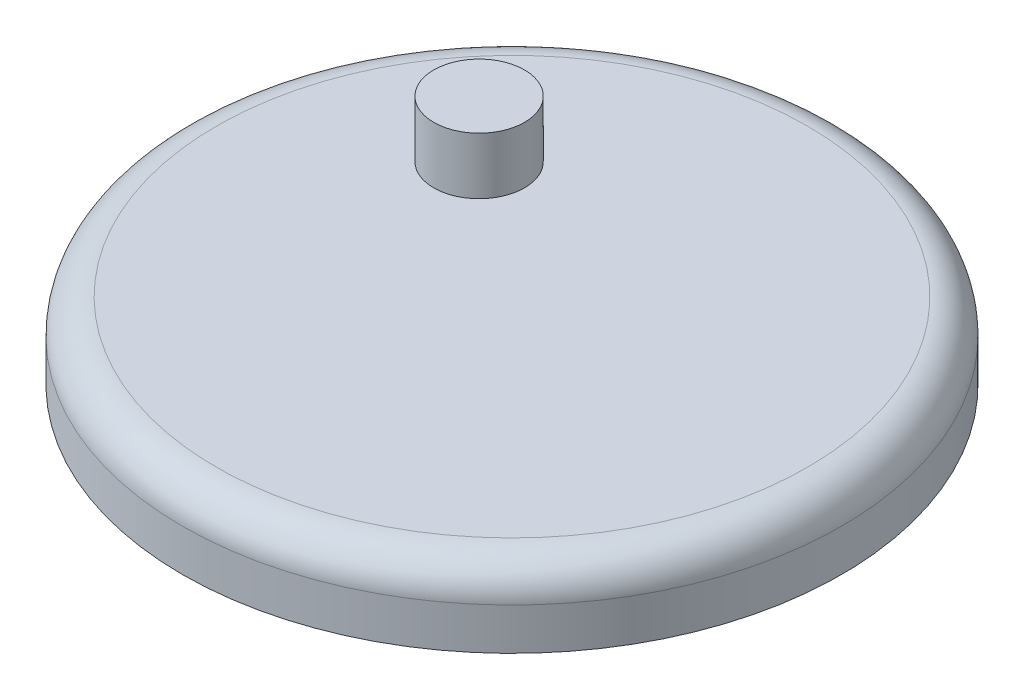
SolidWorks part; units mm, degrees
ref_plane "Front" through (0, 0, 0) normal (0, 0, 1) x (1, 0, 0)
ref_plane "Top" through (0, 0, 0) normal (0, 1, 0) x (1, 0, 0)
ref_plane "Right" through (0, 0, 0) normal (1, 0, 0) x (0, 0, -1)
sketch "草图1" plane through (0, 0, 0) normal (0, 0, 1) x (1, 0, 0)
  line L0 (0, 0) -> (29.0332, 0)
  line L1 (29.0332, 0) -> (29.0332, 6.6883)
  line L2 (29.0332, 6.6883) -> (0, 6.6883)
  line L3 (0, 6.6883) -> (0, 0) construction
  line L4 (0, 0) -> (0, 6.6883)
revolve "旋转1" add sketch "草图1" angle 360 about L3
fillet "圆角1" radius 3 1 edges at (0, 6.6883, 29.0332)
sketch "草图2" plane through (0, 6.6883, 0) normal (0, 1, 0) x (1, 0, 0)
  circle A0 centre (-11.7472, 8.8517) radius 4
  dimension "D1" = 8
extrude "凸台-拉伸1" add sketch "草图2" along normal blind 5
shell "抽壳1" thickness 2
